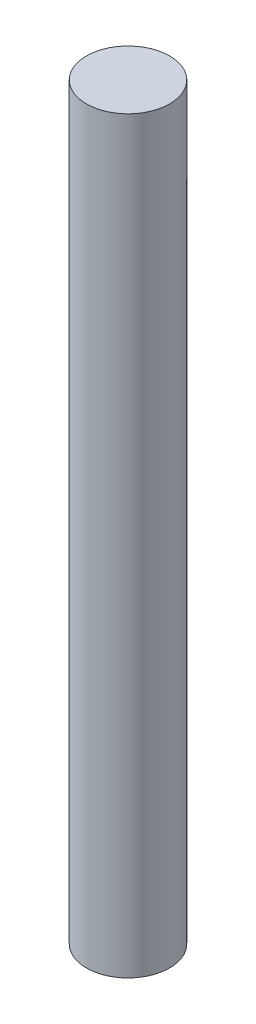
SolidWorks part; units mm, degrees
ref_plane "Front Plane" through (0, 0, 0) normal (0, 0, 1) x (1, 0, 0)
ref_plane "Top Plane" through (0, 0, 0) normal (0, 1, 0) x (1, 0, 0)
ref_plane "Right Plane" through (0, 0, 0) normal (1, 0, 0) x (0, 0, -1)
sketch "Sketch1" plane through (0, 0, 0) normal (0, 1, 0) x (1, 0, 0)
  circle A0 centre (0, 0) radius 5
  dimension "D1" = 10
extrude "Boss-Extrude1" add sketch "Sketch1" along normal blind 90
